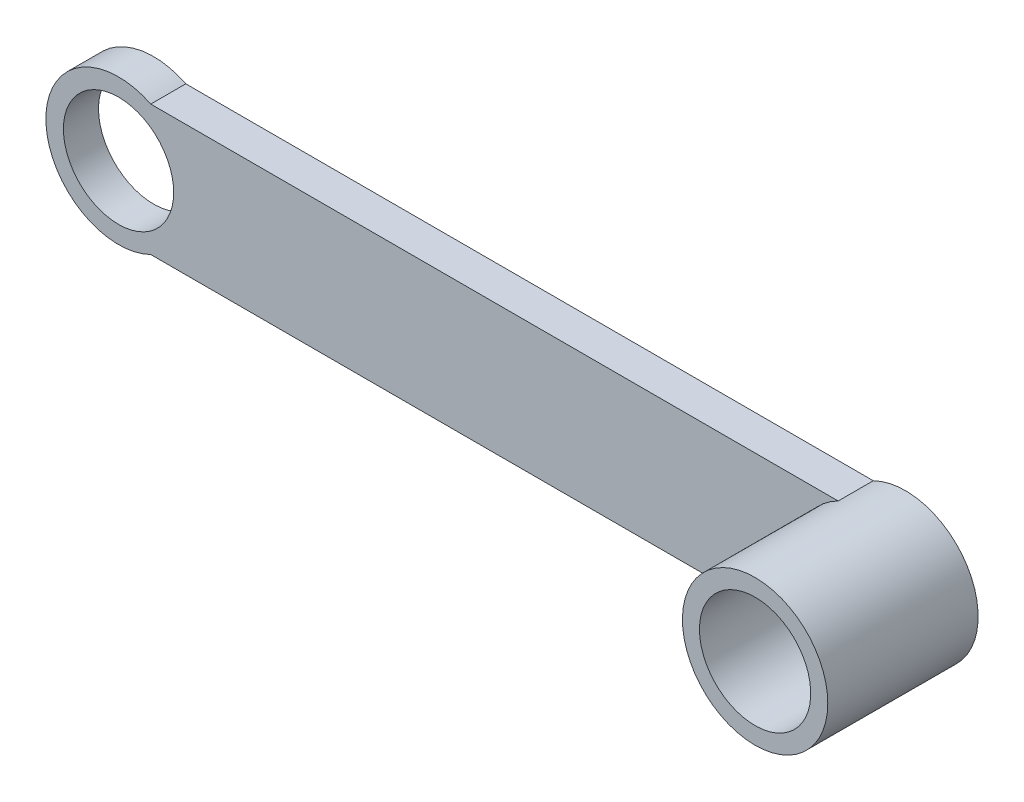
SolidWorks part; units mm, degrees
ref_plane "Front Plane" through (0, 0, 0) normal (0, 0, 1) x (1, 0, 0)
ref_plane "Top Plane" through (0, 0, 0) normal (0, 1, 0) x (1, 0, 0)
ref_plane "Right Plane" through (0, 0, 0) normal (1, 0, 0) x (0, 0, -1)
sketch "Sketch1" plane through (0, 0, 0) normal (0, 0, 1) x (1, 0, 0)
  line L0 (-75, 0) -> (75, 0) construction
  line L2 (-68.5774, 13) -> (68.5774, 13)
  line L3 (-68.5774, 13) -> (-68.5774, -13) construction
  line L4 (-68.5774, -13) -> (68.5774, -13)
  line L5 (68.5774, 13) -> (68.5774, -13) construction
  arc A0 (-68.5774, 13) -> (-68.5774, -13) centre (-75, 0) ccw
  arc A1 (68.5774, -13) -> (68.5774, 13) centre (75, 0) ccw
  point P4 (0, 0)
  point P10 (68.5774, 0)
  dimension "D2" = 29
  dimension "D1" = 150
  dimension "D3" = 26
extrude "Boss-Extrude1" add sketch "Sketch1" along normal blind 7
sketch "Sketch2" plane through (0, 0, 7) normal (0, 0, 1) x (1, 0, 0)
  circle A0 centre (75, 0) radius 14.5
  arc A1 (68.5774, -13) -> (68.5774, 13) centre (75, 0) ccw construction
extrude "Boss-Extrude2" add sketch "Sketch2" along normal blind 23
sketch "Sketch3" plane through (0, 0, 0) normal (0, 0, -1) x (-1, 0, 0)
  circle A0 centre (-75, 0) radius 11
  circle A1 centre (75, 0) radius 11
  dimension "D1" = 22
extrude "Cut-Extrude1" cut sketch "Sketch3" against normal through all
sketch "Sketch4" plane through (0, 0, 0) normal (0, 0, -1) x (-1, 0, 0)
  circle A0 centre (-75, 0) radius 11.1
  dimension "D1" = 22.2
extrude "Cut-Extrude2" cut sketch "Sketch4" against normal through all from offset 7
